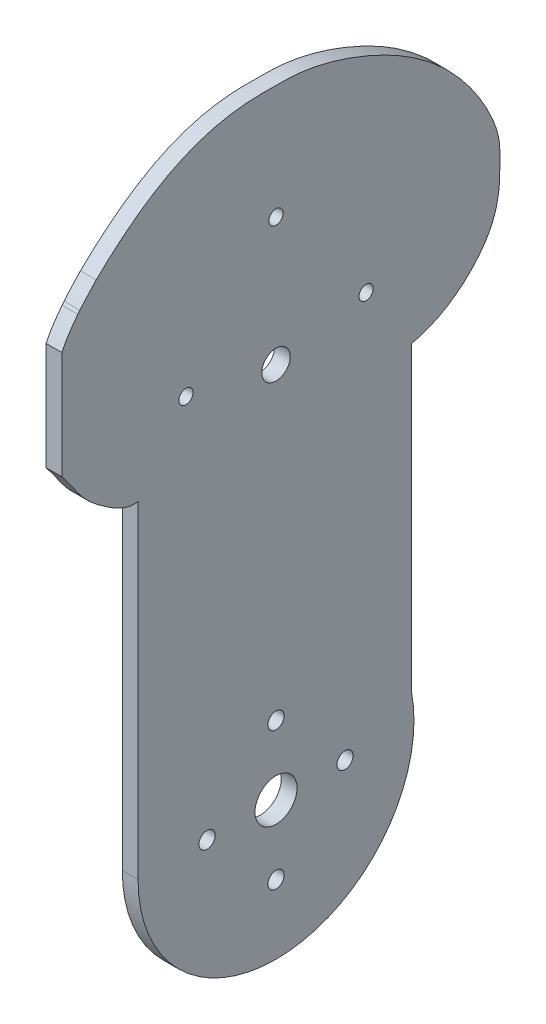
SolidWorks part; units mm, degrees
ref_plane "Plan de face" through (0, 0, 0) normal (0, 0, 1) x (1, 0, 0)
ref_plane "Plan de dessus" through (0, 0, 0) normal (0, 1, 0) x (1, 0, 0)
ref_plane "Plan de droite" through (0, 0, 0) normal (1, 0, 0) x (0, 0, -1)
sketch "Esquisse1" plane through (0, 0, 0) normal (1, 0, 0) x (0, 0, -1)
  line L24 (-40.6082, -16.1449) -> (-40.6083, -16.3483)
  line L25 (0.1651, -90) -> (0.1651, -116.2575) construction
  line L27 (0.1651, 0) -> (0.1651, -90) construction
  line L28 (-26.0924, -27.6543) -> (-26.0924, -90) construction
  line L33 (-26.0924, -90) -> (25.954, -90) construction
  line L34 (25.954, -90) -> (25.954, -27.6542) construction
  line L35 (-40.6082, 4.1425) -> (-40.6082, -12.7)
  line L36 (-26.0924, -27.6543) -> (-26.0924, -90)
  line L37 (25.954, -27.6542) -> (25.954, -90)
  line L38 (-40.6082, -16.1449) -> (-40.6082, -12.7)
  line L39 (-37.9035, 8.4934) -> (-36.4387, 10.3053) construction
  circle A4 centre (-16.9799, -14.9225) radius 1.3525
  arc A7 (-37.1666, 9.4049) -> (-37.5578, 8.9143) centre (-0.9364, -19.8843) ccw
  circle A8 centre (0.1651, -18.2245) radius 2.7051
  circle A9 centre (17.3101, -14.9225) radius 1.3525
  circle A10 centre (0.1651, 6.1035) radius 1.3525
  arc A14 (-26.0924, -90) -> (25.954, -85.0614) centre (0.1651, -90) ccw
  circle A16 centre (0.1651, -103.1288) radius 1.55
  circle A17 centre (-12.9637, -90) radius 1.55
  circle A18 centre (0.1651, -76.8712) radius 1.55
  circle A19 centre (13.2939, -90) radius 1.55
  circle A20 centre (0.1651, -90) radius 4
  spline S5 degree 3 poles (31.4351, 15.2777) (30.2997, 16.3094) (29.1137, 17.2754) (26.6466, 19.0843) (25.3605, 19.9283) (21.4323, 22.2657) (18.7017, 23.5637) (14.4778, 25.2131) (13.0492, 25.7149) (10.8644, 26.3699) (10.1291, 26.5718) (8.6416, 26.9365) (7.8908, 27.0988) (5.638, 27.5124) (4.1274, 27.6937) (2.2253, 27.7687) (1.8441, 27.7755) (1.0809, 27.78) (0.6989, 27.7774) (-0.4463, 27.7791) (-1.2089, 27.7978) (-2.7327, 27.8153) (-3.4921, 27.8063) (-5.0041, 27.74) (-5.757, 27.6849) (-8.0062, 27.4518) (-9.4927, 27.2046) (-11.702, 26.6888) (-12.4349, 26.4915) (-13.8943, 26.0519) (-14.6221, 25.8075) (-16.7654, 25.0122) (-18.1515, 24.4005) (-20.8478, 23.0325) (-22.1587, 22.2775) (-24.7165, 20.6454) (-25.9664, 19.7652) (-28.3913, 17.9197) (-29.5674, 16.9543) (-31.2876, 15.4541) (-31.8538, 14.9457) (-32.9728, 13.9129) (-33.5258, 13.3888) (-34.0661, 12.8498) knots 0 0 0 0 0.0625 0.0625 0.125 0.125 0.25 0.25 0.3125 0.3125 0.34375 0.34375 0.375 0.375 0.4375 0.4375 0.453125 0.453125 0.46875 0.46875 0.5 0.5 0.53125 0.53125 0.5625 0.5625 0.625 0.625 0.65625 0.65625 0.6875 0.6875 0.75 0.75 0.8125 0.8125 0.875 0.875 0.9375 0.9375 0.96875 0.96875 1 1 1 1
  spline S6 degree 3 poles (-40.6083, -16.3483) (-40.3656, -16.6612) (-40.1123, -16.9655) (-39.6302, -17.5937) (-39.4007, -17.9172) (-38.719, -18.8931) (-38.2719, -19.5496) (-37.3385, -20.831) (-36.8555, -21.4585) (-36.0597, -22.3425) (-35.7819, -22.627) (-35.2029, -23.1772) (-34.9007, -23.4435) (-33.9719, -24.2127) (-33.3244, -24.6854) (-32.0108, -25.6045) (-31.3481, -26.0558) (-30.3031, -26.6606) (-29.9483, -26.8487) (-29.2225, -27.185) (-28.8514, -27.3338) (-28.0836, -27.5707) (-27.6853, -27.658) (-27.0907, -27.7154) (-26.8919, -27.7226) (-26.5928, -27.7129) (-26.493, -27.7063) (-26.293, -27.6856) (-26.1927, -27.6705) (-26.0924, -27.6543) knots 0 0 0 0 0.0625 0.0625 0.125 0.125 0.25 0.25 0.375 0.375 0.4375 0.4375 0.5 0.5 0.625 0.625 0.75 0.75 0.8125 0.8125 0.875 0.875 0.9375 0.9375 0.96875 0.96875 0.984375 0.984375 1 1 1 1
  spline S7 degree 3 poles (25.954, -27.6542) (27.1791, -27.4195) (28.3534, -27.0518) (30.0571, -26.3492) (30.6151, -26.0893) (31.7129, -25.5214) (32.2545, -25.2121) (33.8272, -24.2304) (34.814, -23.5021) (36.672, -21.9072) (37.5433, -21.0408) (38.7519, -19.6235) (39.1347, -19.135) (39.851, -18.1314) (40.1855, -17.6153) (40.8014, -16.5506) (41.0826, -16.002) (41.457, -15.1502) (41.5742, -14.8604) (41.7897, -14.2771) (41.888, -13.9835) (42.3347, -12.5068) (42.5462, -11.2963) (42.7176, -9.4515) (42.7506, -8.8307) (42.7729, -7.9005) (42.7754, -7.5904) (42.7756, -6.9702) (42.7721, -6.6601) (42.7721, -6.35) knots 0 0 0 0 0.125 0.125 0.1875 0.1875 0.25 0.25 0.375 0.375 0.5 0.5 0.5625 0.5625 0.625 0.625 0.6875 0.6875 0.71875 0.71875 0.75 0.75 0.875 0.875 0.9375 0.9375 0.96875 0.96875 1 1 1 1
  spline S8 degree 3 poles (42.7721, -6.35) (42.7721, -5.8749) (42.7838, -5.3981) (42.7897, -4.447) (42.7819, -3.973) (42.6725, -2.5632) (42.4992, -1.6375) (42.1063, -0.2679) (41.9541, 0.1856) (41.6148, 1.0877) (41.4301, 1.5303) (40.8449, 2.8393) (40.4166, 3.6895) (39.0468, 6.1905) (38.0131, 7.7873) (36.2917, 10.0821) (35.6885, 10.8307) (34.4365, 12.2817) (33.7862, 12.9857) (33.1121, 13.6686) knots 0 0 0 0 0.0625 0.0625 0.125 0.125 0.25 0.25 0.3125 0.3125 0.375 0.375 0.5 0.5 0.75 0.75 0.875 0.875 1 1 1 1
  spline S9 degree 3 poles (-37.5578, 8.9143) (-38.1429, 8.1702) (-38.7095, 7.4127) (-39.7419, 5.8248) (-40.2031, 4.9988) (-40.6082, 4.1425) knots 0 0 0 0 0.5 0.5 1 1 1 1
  spline S10 degree 3 poles (-34.0661, 12.8498) (-35.1598, 11.6922) (-36.2511, 10.5374) (-37.1666, 9.4049) knots 0 0 0 0 1 1 1 1
  spline S11 degree 2 poles (33.1121, 13.6686) (32.3322, 14.5391) (31.4351, 15.2777) knots 0 0 0 1 1 1
  point P69 (0.1651, -90)
  dimension "D2" = 4
  dimension "D3" = 8
  dimension "D4" = 3.1
  dimension "D1" = 26.2575
extrude "Boss.-Extru.1" add sketch "Esquisse1" along normal blind 3
